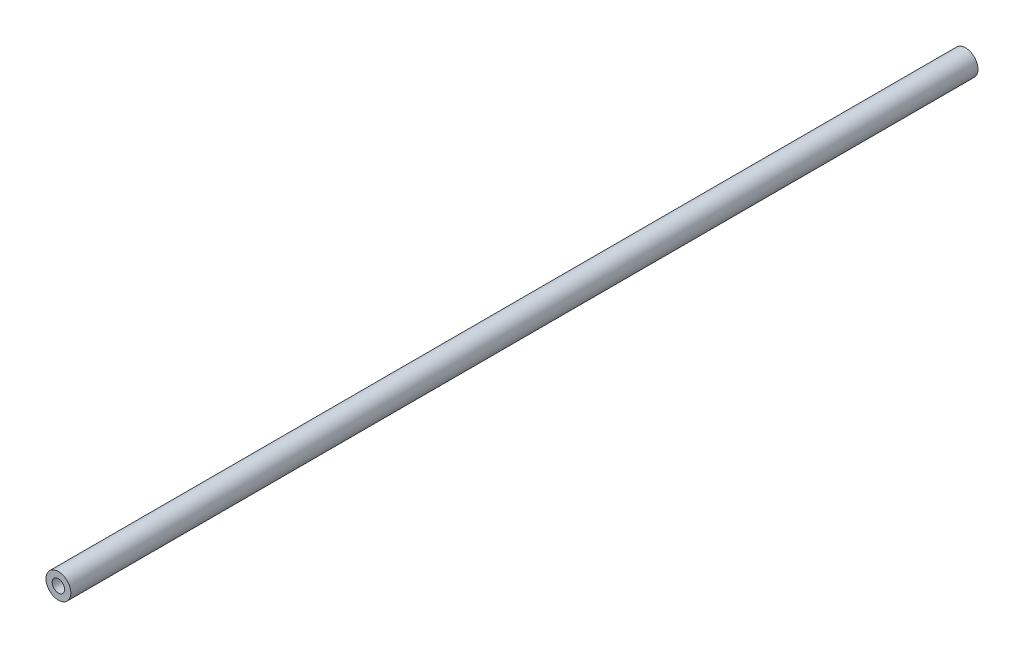
SolidWorks part; units mm, degrees
ref_plane "Front Plane" through (0, 0, 0) normal (0, 0, 1) x (1, 0, 0)
ref_plane "Top Plane" through (0, 0, 0) normal (0, 1, 0) x (1, 0, 0)
ref_plane "Right Plane" through (0, 0, 0) normal (1, 0, 0) x (0, 0, -1)
sketch "Sketch1" plane through (0, 0, 0) normal (0, 0, 1) x (1, 0, 0)
  circle A0 centre (0, 0) radius 4
  circle A1 centre (0, 0) radius 2
  dimension "D1" = 8
  dimension "D2" = 2
extrude "Boss-Extrude1" add sketch "Sketch1" along normal blind 292
